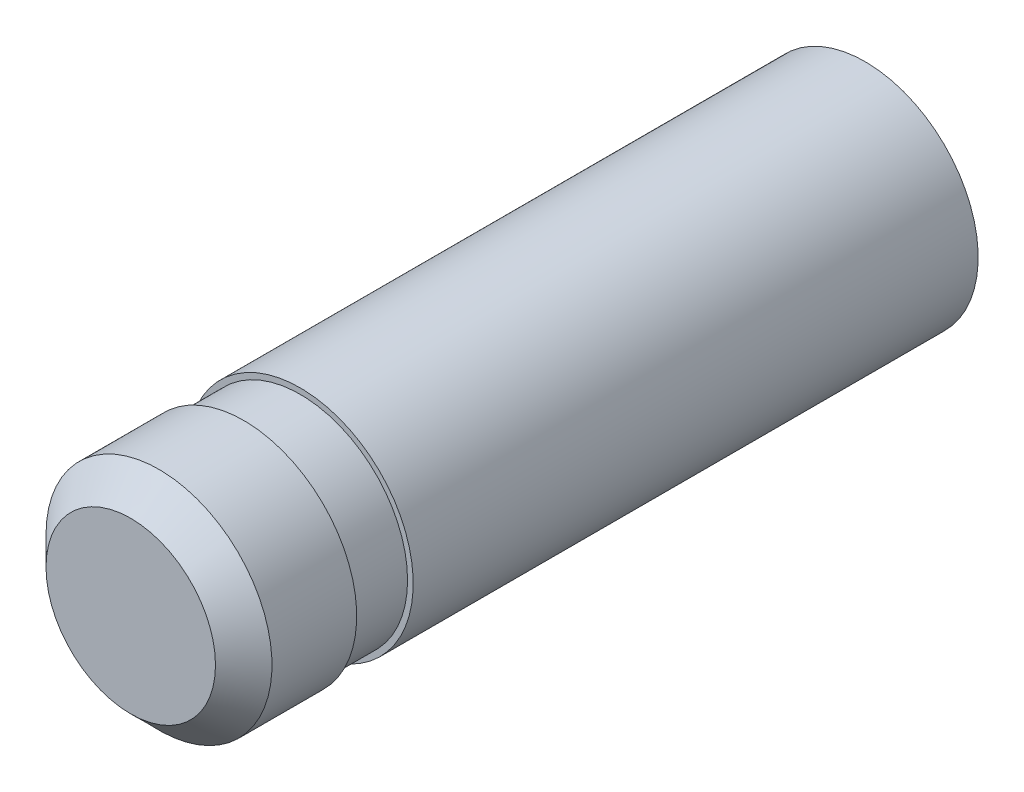
SolidWorks part; units mm, degrees
ref_plane "Ön Düzlem" through (0, 0, 0) normal (0, 0, 1) x (1, 0, 0)
ref_plane "Üst Düzlem" through (0, 0, 0) normal (0, 1, 0) x (1, 0, 0)
ref_plane "Sağ Düzlem" through (0, 0, 0) normal (1, 0, 0) x (0, 0, -1)
sketch "Sketch1" plane through (0, 0, 0) normal (0, 0, 1) x (1, 0, 0)
  circle A0 centre (0, 0) radius 2
extrude "Boss-Extrude1" add sketch "Sketch1" along normal blind 13
sketch "Sketch2" plane through (0, 0, 0) normal (0, 0, -1) x (-1, 0, 0)
  circle A0 centre (0, 0) radius 1.9
extrude "Cut-Extrude1" cut sketch "Sketch2" against normal blind 1 from offset 10 flip side to cut offset against normal yes
chamfer "Chamfer1" distance 0.5 angle 45 1 edges at (2, 0, 13)
scale "Scale1" scale about centroid uniform scaling yes scale factor 1.5
